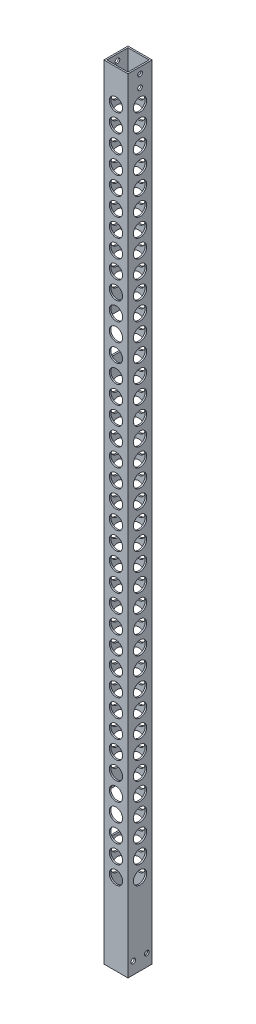
SolidWorks part; units mm, degrees
material "6061-T6 (SS)"
ref_plane "Front Plane" through (0, 0, 0) normal (0, 0, 1) x (1, 0, 0)
ref_plane "Top Plane" through (0, 0, 0) normal (0, 1, 0) x (1, 0, 0)
ref_plane "Right Plane" through (0, 0, 0) normal (1, 0, 0) x (0, 0, -1)
sketch "Sketch1" plane through (0, 0, 0) normal (0, 1, 0) x (1, 0, 0)
  line L1 (-12.7, -12.7) -> (12.7, -12.7)
  line L2 (-12.7, -12.7) -> (-12.7, 12.7)
  line L3 (-12.7, 12.7) -> (12.7, 12.7)
  line L4 (12.7, -12.7) -> (12.7, 12.7)
  line L5 (-12.7, -12.7) -> (12.7, 12.7) construction
  line L6 (-12.7, 12.7) -> (12.7, -12.7) construction
  line L7 (-11.1125, -11.1125) -> (11.1125, -11.1125)
  line L8 (-11.1125, -11.1125) -> (-11.1125, 11.1125)
  line L9 (-11.1125, 11.1125) -> (11.1125, 11.1125)
  line L10 (11.1125, -11.1125) -> (11.1125, 11.1125)
  line L11 (-11.1125, -11.1125) -> (11.1125, 11.1125) construction
  line L12 (-11.1125, 11.1125) -> (11.1125, -11.1125) construction
  point P0 (0, 0)
  point P5 (0, 0)
  dimension "D1" = 25.4
  dimension "D2" = 1.5875
extrude "Boss-Extrude1" add sketch "Sketch1" along normal mid plane 824.611
sketch "Sketch2" plane through (0, 0, 0) normal (1, 0, 0) x (0, 0, -1)
  line L1 (7.1437, -399.6055) -> (-7.1437, -399.6055) construction
  line L4 (-12.7, -412.3055) -> (12.7, -412.3055) construction
  line L6 (0, -399.6055) -> (0, -412.3055) construction
  line L7 (-11.1125, -412.3055) -> (11.1125, -412.3055) construction
  circle A2 centre (-7.1437, -399.6055) radius 2.4765
  circle A3 centre (7.1437, -399.6055) radius 2.4765
  point P18 (0, -412.3055)
  dimension "D1" = 12.7
  dimension "D2" = 4.953
  dimension "D3" = 14.2875
extrude "Cut-Extrude1" cut sketch "Sketch2" against normal through all both and the other way through all
sketch "Sketch3" plane through (0, 0, 0) normal (1, 0, 0) x (0, 0, -1)
  line L0 (0, 412.3055) -> (0, 393.2555) construction
  line L1 (-12.7, 412.3055) -> (12.7, 412.3055) construction
  circle A0 centre (0, 405.9555) radius 2.4765
  circle A1 centre (0, 393.2555) radius 2.4765
  dimension "D3" = 4.953
  dimension "D1" = 6.35
  dimension "D2" = 12.7
extrude "Cut-Extrude2" cut sketch "Sketch3" against normal through all both and the other way through all
sketch "Sketch4" plane through (-12.7, 0, 0) normal (-1, 0, 0) x (0, 0, 1)
  line L0 (0, -412.3055) -> (0, -290.5125) construction
  line L1 (-12.7, -412.3055) -> (12.7, -412.3055) construction
  line L3 (-7.62, -282.8925) -> (7.62, -282.8925)
  line L4 (-7.62, -282.8925) -> (-7.62, -298.1325)
  line L5 (-7.62, -298.1325) -> (7.62, -298.1325)
  line L6 (7.62, -282.8925) -> (7.62, -298.1325)
  line L7 (-7.62, -282.8925) -> (7.62, -298.1325) construction
  line L8 (-7.62, -298.1325) -> (7.62, -282.8925) construction
  dimension "D1" = 114.173
  dimension "D2" = 15.24
extrude "Cut-Extrude3" cut sketch "Sketch4" against normal up to next
fillet "Fillet1" radius 2.54 4 edges at (-11.9063, -282.8925, 7.62) (-11.9062, -282.8925, -7.62) (-11.9063, -298.1325, 7.62) (-11.9063, -298.1325, -7.62)
sketch "Sketch5" plane through (0, 0, 0) normal (0, 0, 1) x (1, 0, 0)
  line L0 (0, 412.3055) -> (0, 298.7938) construction
  line L1 (-12.7, 412.3055) -> (12.7, 412.3055) construction
  circle A0 centre (0, 380.5555) radius 2.4892
  circle A1 centre (0, 361.5055) radius 2.4892
  circle A2 centre (0, 342.4555) radius 2.4892
  circle A3 centre (0, 323.4055) radius 2.4892
  circle A4 centre (0, 304.3555) radius 2.4892
  circle A5 centre (0, 285.3055) radius 2.4892
  circle A6 centre (0, 266.2555) radius 2.4892
  circle A7 centre (0, 247.2055) radius 2.4892
  circle A8 centre (0, 228.1555) radius 2.4892
  circle A9 centre (0, 209.1055) radius 2.4892
  circle A10 centre (0, 190.0555) radius 2.4892
  circle A11 centre (0, 171.0055) radius 2.4892
  circle A12 centre (0, 151.9555) radius 2.4892
  circle A13 centre (0, 132.9055) radius 2.4892
  circle A14 centre (0, 113.8555) radius 2.4892
  dimension "D1" = 4.9784
  dimension "D2" = 31.75
  dimension "D4" = 19.05
  dimension "D3" = 15
extrude "Cut-Extrude4" cut sketch "Sketch5" against normal through all both and the other way through all
sketch "Sketch6" plane through (0, 0, 12.7) normal (0, 0, 1) x (1, 0, 0)
  line L0 (0, 378.0155) -> (0, 412.3055) construction
  line L1 (-12.7, 412.3055) -> (12.7, 412.3055) construction
  circle A0 centre (0, 378.0155) radius 6.985
  dimension "D1" = 13.97
  dimension "D2" = 34.29
extrude "Cut-Extrude5" cut sketch "Sketch6" against normal blind 2.54
pattern_linear "LPattern1" count 38 spacing 19.05 along (0, -1, 0) of "Cut-Extrude5"
ref_axis "Axis1" through (0, -453.5361, 0) along (0, 1, 0)
pattern_circular "CirPattern1" count 4 over 360 about axis through (0, -453.5361, 0) along (0, 1, 0) skipping 3 of "LPattern1", "Cut-Extrude5"
sketch "Sketch7" plane through (-12.7, 0, 0) normal (-1, 0, 0) x (0, 0, 1)
  line L0 (-9.525, 177.3555) -> (9.525, 177.3555)
  line L1 (-9.525, 177.3555) -> (-9.525, 139.2555)
  line L2 (9.525, 177.3555) -> (9.525, 139.2555)
  line L3 (-9.525, 139.2555) -> (9.525, 139.2555)
  line L4 (0, -453.5361) -> (0, 453.5361) construction
  line L5 (-12.7, 412.3055) -> (12.7, 412.3055) construction
  line L6 (-9.525, -292.5445) -> (9.525, -292.5445)
  line L7 (-9.525, -292.5445) -> (-9.525, -254.4445)
  line L8 (9.525, -292.5445) -> (9.525, -254.4445)
  line L9 (-9.525, -254.4445) -> (9.525, -254.4445)
  point P0 (0, 177.3555)
  point P7 (0, -292.5445)
  dimension "D1" = 38.1
  dimension "D2" = 234.95
  dimension "D3" = 666.75
  dimension "D4" = 19.05
extrude "Cut-Extrude6" cut sketch "Sketch7" against normal blind 2.54
sketch "Sketch8" plane through (-12.7, 0, 0) normal (-1, 0, 0) x (0, 0, 1)
  circle A0 centre (0, 378.0155) radius 6.985 construction
  circle A1 centre (0, 378.0155) radius 6.985
extrude "Cut-Extrude7" cut sketch "Sketch8" against normal blind 2.54
pattern_linear "LPattern2" count 38 spacing 19.05 along (0, -1, 0) skipping (10, 0), (11, 0), (12, 0), (13, 0), (33, 0), (34, 0), (35, 0) of "Cut-Extrude7"
sketch "Sketch9" plane through (0, 412.3055, 0) normal (0, 1, 0) x (1, 0, 0)
  line L0 (12.7, 12.7) -> (38.1, 12.7) construction
  line L1 (-12.7, 12.7) -> (-12.7, 38.1) construction
  line L2 (-12.7, 12.7) -> (-12.7, -12.7) construction
  line L4 (12.7, 12.7) -> (-12.7, 12.7) construction
  dimension "D1" = 25.4
sketch "Sketch10" plane through (-12.7, 0, 0) normal (-1, 0, 0) x (0, 0, 1)
  line L0 (10.668, -412.3055) -> (-10.668, -412.3055) construction
  line L1 (10.668, -412.3055) -> (10.668, -417.3855) construction
  line L2 (-10.668, -412.3055) -> (-10.668, -417.3855) construction
  line L3 (10.668, -417.3855) -> (-10.668, -417.3855) construction
  line L4 (-12.7, -412.3055) -> (12.7, -412.3055) construction
  line L5 (12.7, 412.376) -> (12.7, 414.662) construction
  line L6 (12.7, 412.3055) -> (12.7, -412.3055) construction
  dimension "D1" = 2.032
  dimension "D2" = 2.032
  dimension "D3" = 5.08
  dimension "D4" = 2.286
sketch "Sketch11" plane through (0, 0, 12.7) normal (0, 0, 1) x (1, 0, 0)
  line L0 (-10.668, -412.3055) -> (10.668, -412.3055) construction
  line L1 (-10.668, -412.3055) -> (-10.668, -417.3855) construction
  line L2 (10.668, -412.3055) -> (10.668, -417.3855) construction
  line L3 (-10.668, -417.3855) -> (10.668, -417.3855) construction
  line L4 (-12.7, -412.3055) -> (12.7, -412.3055) construction
  dimension "D1" = 2.032
  dimension "D2" = 2.032
  dimension "D3" = 5.08
ref_plane "Plane1" through (0, 414.662, 0) normal (0, 1, 0) x (1, 0, 0)
sketch "Sketch12" plane through (0, 414.662, 0) normal (0, 1, 0) x (1, 0, 0)
  line L0 (-12.7, -12.7) -> (-38.1, -12.7) construction
  line L1 (-12.7, -12.7) -> (12.7, -12.7) construction
  dimension "D1" = 25.4
